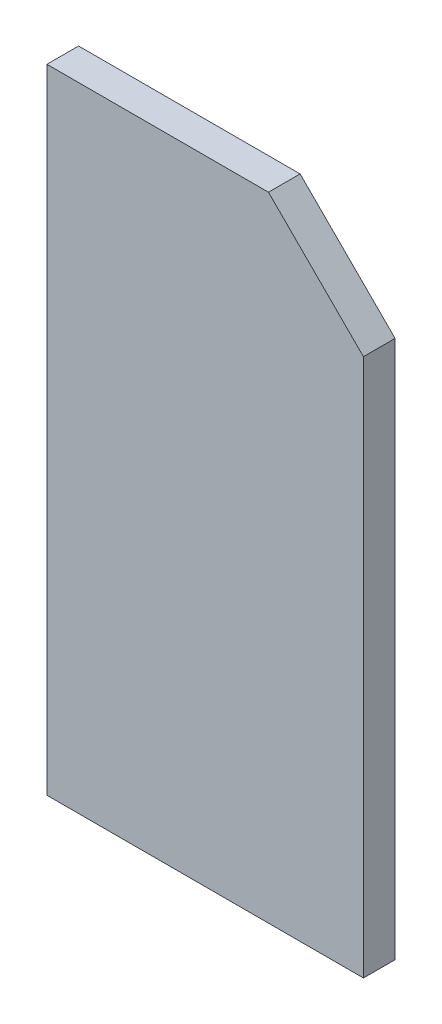
SolidWorks part; units mm, degrees
ref_plane "Front Plane" through (0, 0, 0) normal (0, 0, 1) x (1, 0, 0)
ref_plane "Top Plane" through (0, 0, 0) normal (0, 1, 0) x (1, 0, 0)
ref_plane "Right Plane" through (0, 0, 0) normal (1, 0, 0) x (0, 0, -1)
sketch "Sketch3" plane through (0, 0, 0) normal (0, 0, 1) x (1, 0, 0)
  line L0 (250, 500) -> (250, 0)
  line L1 (0, 0) -> (250, 0)
  line L2 (0, 0) -> (0, 500)
  line L3 (0, 500) -> (250, 500)
  dimension "D1" = 250
  dimension "D2" = 500
extrude "Boss-Extrude2" add sketch "Sketch3" along normal blind 25
sketch "Sketch4" plane through (0, 0, 25) normal (0, 0, 1) x (1, 0, 0)
  line L0 (175, 500) -> (250, 425)
  line L1 (250, 500) -> (0, 500) construction
  line L2 (250, 0) -> (250, 500) construction
  line L3 (250, 425) -> (250, 500)
  line L4 (250, 500) -> (175, 500)
  dimension "D1" = 75
  dimension "D2" = 75
extrude "Cut-Extrude1" cut sketch "Sketch4" against normal blind 25.4
